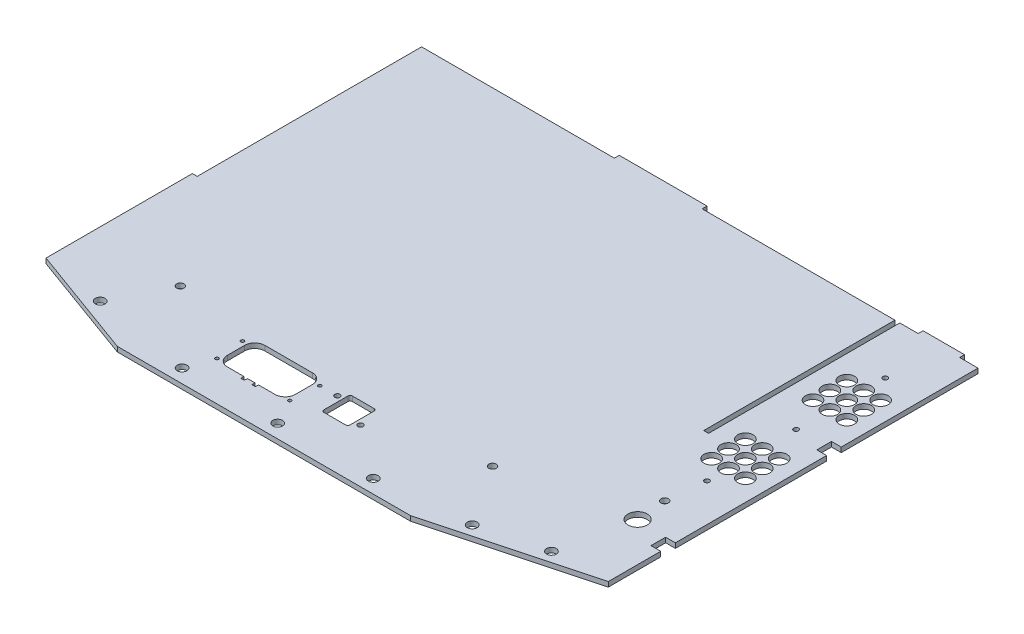
SolidWorks part; units mm, degrees
material "6061-T6 (SS)"
ref_plane "X-Y Datum" through (0, 0, 0) normal (0, 0, 1) x (1, 0, 0)
ref_plane "X-Z Datum" through (0, 0, 0) normal (0, 1, 0) x (1, 0, 0)
ref_plane "Y-Z Datum" through (0, 0, 0) normal (1, 0, 0) x (0, 0, -1)
sketch "Sketch1" plane through (0, 0, 0) normal (0, 0, 1) x (1, 0, 0)
  line L1 (-154.0408, -1.5875) -> (154.0408, -1.5875)
  line L2 (-154.0408, -1.5875) -> (-154.0408, 1.5875)
  line L3 (-154.0408, 1.5875) -> (154.0408, 1.5875)
  line L4 (154.0408, -1.5875) -> (154.0408, 1.5875)
  line L5 (-154.0408, -1.5875) -> (154.0408, 1.5875) construction
  line L6 (-154.0408, 1.5875) -> (154.0408, -1.5875) construction
  point P0 (0, 0)
  dimension "D1" = 3.175
  dimension "D2" = 308.0817
extrude "Boss-Extrude1" add sketch "Sketch1" along normal blind 267.83
sketch "Sketch3" plane through (154.0408, 0, 0) normal (1, 0, 0) x (0, 0, -1)
  line L9 (0, -1.5875) -> (0, 1.5875)
  line L10 (0, 1.5875) -> (-267.83, 1.5875)
  line L11 (-267.83, 1.5875) -> (-267.83, -1.5875)
  line L12 (-267.83, -1.5875) -> (0, -1.5875)
  line L13 (0, -1.5875) -> (0, 1.5875)
  line L14 (0, 1.5875) -> (-267.83, 1.5875)
  line L15 (-267.83, 1.5875) -> (-267.83, -1.5875)
  line L16 (-267.83, -1.5875) -> (0, -1.5875)
  dimension "D1" = 0
extrude "Boss-Extrude3" add sketch "Sketch3" along normal blind 3.175
sketch "Sketch4" plane through (0, 0, 267.83) normal (0, 0, 1) x (1, 0, 0)
  line L1 (157.2158, -1.5875) -> (208.1047, -1.5875)
  line L2 (157.2158, -1.5875) -> (157.2158, 1.5875)
  line L3 (157.2158, 1.5875) -> (208.1047, 1.5875)
  line L4 (208.1047, -1.5875) -> (208.1047, 1.5875)
  dimension "D1" = 3.175
  dimension "D2" = 50.8889
extrude "Boss-Extrude4" add sketch "Sketch4" against normal blind 267.83
sketch "Sketch6" plane through (0, 1.5875, 0) normal (0, 1, 0) x (1, 0, 0)
  line L0 (106.5047, -267.83) -> (106.5047, -228.46)
  line L1 (208.1047, -267.83) -> (-154.0408, -267.83) construction
  line L2 (208.1047, -228.46) -> (106.5047, -228.46)
  line L3 (208.1047, 0) -> (208.1047, -267.83) construction
  line L5 (106.5047, -267.83) -> (208.1047, -240.6064)
  line L7 (208.1047, -228.46) -> (208.1047, -240.6064)
  line L8 (208.1047, 0) -> (208.1047, -267.83) construction
  line L9 (208.1047, -267.83) -> (-154.0408, -267.83) construction
  line M9 (-154.0408, -267.83) -> (208.1047, -267.83)
  line M10 (208.1047, -267.83) -> (208.1047, 0)
  dimension "D1" = 39.37
  dimension "D2" = 101.6
  dimension "D3" = 15
extrude "Cut-Extrude1" cut sketch "Sketch6" against normal through all contours L5 M9 M10
sketch "Sketch19" plane through (0, 1.5875, 0) normal (0, 1, 0) x (1, 0, 0)
  line L0 (208.1047, 0) -> (208.1047, -240.6064) construction
  line L1 (208.1047, 0) -> (-154.0408, 0) construction
  line L3 (164.1047, -82.5) -> (204.1047, -82.5)
  line L4 (164.1047, -82.5) -> (164.1047, -42.5)
  line L5 (164.1047, -42.5) -> (204.1047, -42.5)
  line L6 (204.1047, -82.5) -> (204.1047, -42.5)
  line L7 (164.1047, -82.5) -> (204.1047, -42.5) construction
  line L8 (164.1047, -42.5) -> (204.1047, -82.5) construction
  circle A0 centre (172.4867, -49.7748) radius 5
  dimension "D5" = 10
  dimension "D6" = 7.2748
  dimension "D1" = 40
  dimension "D2" = 40
  dimension "D3" = 42.5
  dimension "D4" = 8.382
  dimension "D7" = 4
extrude "Cut-Extrude5" cut sketch "Sketch19" against normal through all contours A0
pattern_linear "LPattern1" count 3 spacing 11 along (1, 0, 0) of "Cut-Extrude5"
pattern_linear "LPattern2" count 3 spacing 11 along (0, 0, 1) of "LPattern1", "Cut-Extrude5"
pattern_linear "LPattern3" count 2 spacing 66 along (0, 0, 1) of "LPattern2", "Cut-Extrude5", "LPattern1"
sketch "Sketch21" plane through (-154.0408, 0, 0) normal (-1, 0, 0) x (0, 0, 1)
  line L14 (0, -1.5875) -> (267.83, -1.5875)
  line L15 (267.83, -1.5875) -> (267.83, 1.5875)
  line L16 (267.83, 1.5875) -> (0, 1.5875)
  line L17 (0, 1.5875) -> (0, -1.5875)
  line L18 (0, -1.5875) -> (267.83, -1.5875)
  line L20 (267.83, 1.5875) -> (0, 1.5875)
  line L21 (0, 1.5875) -> (0, -1.5875)
  line L22 (267.83, -1.5875) -> (267.83, 1.5875)
  dimension "D1" = 0
extrude "Boss-Extrude5" add sketch "Sketch21" along normal blind 3.175
sketch "Sketch11" plane through (0, -1.5875, 0) normal (0, -1, 0) x (1, 0, 0)
  line L0 (-84.2547, 267.83) -> (-84.2547, 241.2743)
  line L3 (-157.2158, 267.83) -> (106.5047, 267.83) construction
  line L4 (-157.2158, 241.2743) -> (-84.2547, 267.83)
  line L5 (-157.2158, 241.2743) -> (-84.2547, 241.2743)
  line L7 (-157.2158, 0) -> (-157.2158, 267.83) construction
  dimension "D1" = 26.5557
  dimension "D2" = 20
extrude "Cut-Extrude3" cut sketch "Sketch11" against normal through all
sketch "Sketch36" plane through (0, 1.5875, 0) normal (0, 1, 0) x (1, 0, 0)
  circle A1 centre (183.4867, -35.7748) radius 2.4 construction
  circle A2 centre (183.4867, -35.7748) radius 1.5875
  dimension "D1" = 3.175
extrude "Cut-Extrude12" cut sketch "Sketch36" against normal through all both and the other way through all
pattern_linear "LPattern4" count 3 spacing 58 along (0, 0, 1) of "Cut-Extrude12"
sketch "Sketch38" plane through (0, 1.5875, 0) normal (0, 1, 0) x (1, 0, 0)
  point P0 (180.965, -176.776)
  point P1 (105.4291, -213.285)
  point P2 (105.4291, -213.285)
  point P3 (-97.7709, -213.285)
hole_wizard "M4 Clearance Hole1" positions "Sketch38" profile "Sketch39" hole size "M4" standard "ANSI Metric" end condition through all
sketch "Sketch39" plane through (180.965, 1.5875, 176.776) normal (1, 0, 0) x (0, 0, 1)
  line L0 (0, 0) -> (0, 3.175)
  line L1 (0, 3.175) -> (2.4, 3.175)
  line L2 (2.4, 3.175) -> (2.4, 0)
  line L5 (2.4, 0) -> (0, 0)
  line L11 (0, -6.35) -> (0, 107.95) construction
  dimension "Thru Hole Dia." = 4.8
  dimension "Thru Hole Depth" = 3.175
sketch "Sketch40" plane through (0, 1.5875, 0) normal (0, 1, 0) x (1, 0, 0)
  circle A0 centre (172.5447, -242.093) radius 3.175
  circle A1 centre (131.9047, -252.9824) radius 3.175
  circle A2 centre (73.4847, -258.94) radius 3.175
  circle A3 centre (11.2547, -258.94) radius 3.175
  circle A4 centre (-50.9753, -258.94) radius 3.175
  circle A5 centre (-115.3222, -247.9214) radius 3.175
  point P0 (-115.3222, -247.9214)
  point P1 (-50.9753, -258.94)
  point P3 (11.2547, -258.94)
  point P5 (73.4847, -258.94)
  point P7 (131.9047, -252.9824)
  point P9 (172.5447, -242.093)
  dimension "D1" = 6.35
extrude "Cut-Extrude13" cut sketch "Sketch40" against normal through all
sketch "Sketch41" plane through (0, 1.5875, 0) normal (0, 1, 0) x (1, 0, 0)
  line L0 (-25.8051, -243.2308) -> (-25.6301, -245.2308) construction
  line L1 (-25.6301, -245.2308) -> (-24.1801, -245.2308) construction
  line L2 (-24.1801, -245.2308) -> (-24.0051, -243.2308) construction
  line L3 (-18.4301, -245.2308) -> (-16.9801, -245.2308) construction
  line L4 (-16.9801, -245.2308) -> (-16.8051, -243.2308) construction
  line L5 (-18.6051, -243.2308) -> (-18.4301, -245.2308) construction
  line L6 (-16.8051, -243.2308) -> (-5.8051, -243.2308) construction
  line L7 (0.3949, -237.0308) -> (0.3949, -225.8308) construction
  line L8 (-5.8051, -219.6308) -> (-36.8051, -219.6308) construction
  line L9 (-43.0051, -225.8308) -> (-43.0051, -237.0308) construction
  line L10 (-36.8051, -243.2308) -> (-25.8051, -243.2308) construction
  line L11 (-24.0051, -243.2308) -> (-18.6051, -243.2308) construction
  line L12 (-25.8051, -243.2308) -> (-25.6301, -245.2308) construction
  line L13 (-25.6301, -245.2308) -> (-24.1801, -245.2308) construction
  line L14 (-24.1801, -245.2308) -> (-24.0051, -243.2308) construction
  line L15 (-18.4301, -245.2308) -> (-16.9801, -245.2308) construction
  line L16 (-16.9801, -245.2308) -> (-16.8051, -243.2308) construction
  line L17 (-18.6051, -243.2308) -> (-18.4301, -245.2308) construction
  line L18 (-16.8051, -243.2308) -> (-5.8051, -243.2308) construction
  line L19 (0.3949, -237.0308) -> (0.3949, -225.8308) construction
  line L20 (-5.8051, -219.6308) -> (-36.8051, -219.6308) construction
  line L21 (-43.0051, -225.8308) -> (-43.0051, -237.0308) construction
  line L22 (-36.8051, -243.2308) -> (-25.8051, -243.2308) construction
  line L23 (-24.0051, -243.2308) -> (-18.6051, -243.2308) construction
  line L24 (20.242, -220.3508) -> (34.292, -220.3508) construction
  line L25 (34.292, -219.7008) -> (20.242, -219.7008) construction
  line L26 (19.142, -220.8008) -> (19.142, -236.3508) construction
  line L27 (19.792, -236.3508) -> (19.792, -220.8008) construction
  line L28 (20.242, -237.4508) -> (34.292, -237.4508) construction
  line L29 (34.292, -236.8008) -> (20.242, -236.8008) construction
  line L30 (34.742, -220.8008) -> (34.742, -236.3508) construction
  line L31 (35.392, -236.3508) -> (35.392, -220.8008) construction
  line L32 (20.242, -220.3508) -> (34.292, -220.3508) construction
  line L33 (34.292, -219.7008) -> (20.242, -219.7008) construction
  line L34 (19.142, -220.8008) -> (19.142, -236.3508) construction
  line L35 (19.792, -236.3508) -> (19.792, -220.8008) construction
  line L36 (20.242, -237.4508) -> (34.292, -237.4508) construction
  line L37 (34.292, -236.8008) -> (20.242, -236.8008) construction
  line L38 (34.742, -220.8008) -> (34.742, -236.3508) construction
  line L39 (35.392, -236.3508) -> (35.392, -220.8008) construction
  line L40 (15.267, -225.0758) -> (15.267, -223.0758) construction
  line L41 (39.267, -234.0758) -> (39.267, -232.0758) construction
  line L42 (-26.1542, -243.6118) -> (-25.9792, -245.6118)
  line L43 (-25.9792, -245.6118) -> (-23.8309, -245.6118)
  line L44 (-23.8309, -245.6118) -> (-23.656, -243.6118)
  line L45 (-23.656, -243.6118) -> (-18.9542, -243.6118)
  line L46 (-18.9542, -243.6118) -> (-18.7792, -245.6118)
  line L47 (-18.7792, -245.6118) -> (-16.6309, -245.6118)
  line L48 (-16.6309, -245.6118) -> (-16.456, -243.6118)
  line L49 (-16.456, -243.6118) -> (-5.8051, -243.6118)
  line L50 (0.7759, -237.0308) -> (0.7759, -225.8308)
  line L51 (-5.8051, -219.2498) -> (-36.8051, -219.2498)
  line L52 (-43.3861, -225.8308) -> (-43.3861, -237.0308)
  line L53 (-36.8051, -243.6118) -> (-26.1542, -243.6118)
  line L54 (18.761, -220.8008) -> (18.761, -236.3508)
  line L55 (20.242, -237.8318) -> (34.292, -237.8318)
  line L56 (35.773, -236.3508) -> (35.773, -220.8008)
  line L57 (34.292, -219.3198) -> (20.242, -219.3198)
  spline S0 degree 3 poles (-5.8051, -243.2308) (-2.1732, -243.2308) (0.3949, -240.6627) (0.3949, -237.0308) knots 0 0 0 0 1 1 1 1 weights 1 0.804738 0.804738 1 construction
  spline S1 degree 3 poles (0.3949, -225.8308) (0.3949, -222.1989) (-2.1732, -219.6308) (-5.8051, -219.6308) knots 0 0 0 0 1 1 1 1 weights 1 0.804738 0.804738 1 construction
  spline S2 degree 3 poles (-36.8051, -219.6308) (-40.4369, -219.6308) (-43.0051, -222.1989) (-43.0051, -225.8308) knots 0 0 0 0 1 1 1 1 weights 1 0.804738 0.804738 1 construction
  spline S3 degree 3 poles (-43.0051, -237.0308) (-43.0051, -240.6627) (-40.4369, -243.2308) (-36.8051, -243.2308) knots 0 0 0 0 1 1 1 1 weights 1 0.804738 0.804738 1 construction
  spline S4 degree 3 poles (-5.8051, -243.2308) (-2.1732, -243.2308) (0.3949, -240.6627) (0.3949, -237.0308) knots 0 0 0 0 1 1 1 1 weights 1 0.804738 0.804738 1 construction
  spline S5 degree 3 poles (0.3949, -225.8308) (0.3949, -222.1989) (-2.1732, -219.6308) (-5.8051, -219.6308) knots 0 0 0 0 1 1 1 1 weights 1 0.804738 0.804738 1 construction
  spline S6 degree 3 poles (-36.8051, -219.6308) (-40.4369, -219.6308) (-43.0051, -222.1989) (-43.0051, -225.8308) knots 0 0 0 0 1 1 1 1 weights 1 0.804738 0.804738 1 construction
  spline S7 degree 3 poles (-43.0051, -237.0308) (-43.0051, -240.6627) (-40.4369, -243.2308) (-36.8051, -243.2308) knots 0 0 0 0 1 1 1 1 weights 1 0.804738 0.804738 1 construction
  spline S8 degree 3 poles (34.292, -220.3508) (34.5556, -220.3508) (34.742, -220.5372) (34.742, -220.8008) knots 0 0 0 0 1 1 1 1 weights 1 0.804738 0.804738 1 construction
  spline S9 degree 3 poles (35.392, -220.8008) (35.392, -220.1564) (34.9364, -219.7008) (34.292, -219.7008) knots 0 0 0 0 1 1 1 1 weights 1 0.804738 0.804738 1 construction
  spline S10 degree 3 poles (20.242, -219.7008) (19.5976, -219.7008) (19.142, -220.1564) (19.142, -220.8008) knots 0 0 0 0 1 1 1 1 weights 1 0.804738 0.804738 1 construction
  spline S11 degree 3 poles (19.792, -220.8008) (19.792, -220.5372) (19.9784, -220.3508) (20.242, -220.3508) knots 0 0 0 0 1 1 1 1 weights 1 0.804738 0.804738 1 construction
  spline S12 degree 3 poles (19.142, -236.3508) (19.142, -236.9952) (19.5976, -237.4508) (20.242, -237.4508) knots 0 0 0 0 1 1 1 1 weights 1 0.804738 0.804738 1 construction
  spline S13 degree 3 poles (20.242, -236.8008) (19.9784, -236.8008) (19.792, -236.6144) (19.792, -236.3508) knots 0 0 0 0 1 1 1 1 weights 1 0.804738 0.804738 1 construction
  spline S14 degree 3 poles (34.292, -237.4508) (34.9364, -237.4508) (35.392, -236.9952) (35.392, -236.3508) knots 0 0 0 0 1 1 1 1 weights 1 0.804738 0.804738 1 construction
  spline S15 degree 3 poles (34.742, -236.3508) (34.742, -236.6144) (34.5556, -236.8008) (34.292, -236.8008) knots 0 0 0 0 1 1 1 1 weights 1 0.804738 0.804738 1 construction
  spline S16 degree 3 poles (34.292, -220.3508) (34.5556, -220.3508) (34.742, -220.5372) (34.742, -220.8008) knots 0 0 0 0 1 1 1 1 weights 1 0.804738 0.804738 1 construction
  spline S17 degree 3 poles (35.392, -220.8008) (35.392, -220.1564) (34.9364, -219.7008) (34.292, -219.7008) knots 0 0 0 0 1 1 1 1 weights 1 0.804738 0.804738 1 construction
  spline S18 degree 3 poles (20.242, -219.7008) (19.5976, -219.7008) (19.142, -220.1564) (19.142, -220.8008) knots 0 0 0 0 1 1 1 1 weights 1 0.804738 0.804738 1 construction
  spline S19 degree 3 poles (19.792, -220.8008) (19.792, -220.5372) (19.9784, -220.3508) (20.242, -220.3508) knots 0 0 0 0 1 1 1 1 weights 1 0.804738 0.804738 1 construction
  spline S20 degree 3 poles (19.142, -236.3508) (19.142, -236.9952) (19.5976, -237.4508) (20.242, -237.4508) knots 0 0 0 0 1 1 1 1 weights 1 0.804738 0.804738 1 construction
  spline S21 degree 3 poles (20.242, -236.8008) (19.9784, -236.8008) (19.792, -236.6144) (19.792, -236.3508) knots 0 0 0 0 1 1 1 1 weights 1 0.804738 0.804738 1 construction
  spline S22 degree 3 poles (34.292, -237.4508) (34.9364, -237.4508) (35.392, -236.9952) (35.392, -236.3508) knots 0 0 0 0 1 1 1 1 weights 1 0.804738 0.804738 1 construction
  spline S23 degree 3 poles (34.742, -236.3508) (34.742, -236.6144) (34.5556, -236.8008) (34.292, -236.8008) knots 0 0 0 0 1 1 1 1 weights 1 0.804738 0.804738 1 construction
  spline S24 degree 3 poles (-47.5901, -224.1308) (-47.5901, -221.9608) (-45.4201, -221.9608) (-45.4201, -224.1308) knots 0 0 0 0 1 1 1 1 weights 1 0.333333 0.333333 1 construction
  spline S25 degree 3 poles (-45.4201, -224.1308) (-45.4201, -226.3008) (-47.5901, -226.3008) (-47.5901, -224.1308) knots 0 0 0 0 1 1 1 1 weights 1 0.333333 0.333333 1 construction
  spline S26 degree 3 poles (-43.9201, -242.2308) (-43.9201, -244.4008) (-46.0901, -244.4008) (-46.0901, -242.2308) knots 0 0 0 0 1 1 1 1 weights 1 0.333333 0.333333 1 construction
  spline S27 degree 3 poles (-46.0901, -242.2308) (-46.0901, -240.0608) (-43.9201, -240.0608) (-43.9201, -242.2308) knots 0 0 0 0 1 1 1 1 weights 1 0.333333 0.333333 1 construction
  spline S28 degree 3 poles (3.4799, -242.2308) (3.4799, -244.4008) (1.3099, -244.4008) (1.3099, -242.2308) knots 0 0 0 0 1 1 1 1 weights 1 0.333333 0.333333 1 construction
  spline S29 degree 3 poles (1.3099, -242.2308) (1.3099, -240.0608) (3.4799, -240.0608) (3.4799, -242.2308) knots 0 0 0 0 1 1 1 1 weights 1 0.333333 0.333333 1 construction
  spline S30 degree 3 poles (4.9799, -224.1308) (4.9799, -226.3008) (2.8099, -226.3008) (2.8099, -224.1308) knots 0 0 0 0 1 1 1 1 weights 1 0.333333 0.333333 1 construction
  spline S31 degree 3 poles (2.8099, -224.1308) (2.8099, -221.9608) (4.9799, -221.9608) (4.9799, -224.1308) knots 0 0 0 0 1 1 1 1 weights 1 0.333333 0.333333 1 construction
  spline S32 degree 3 poles (-47.5901, -224.1308) (-47.5901, -221.9608) (-45.4201, -221.9608) (-45.4201, -224.1308) knots 0 0 0 0 1 1 1 1 weights 1 0.333333 0.333333 1
  spline S33 degree 3 poles (-45.4201, -224.1308) (-45.4201, -226.3008) (-47.5901, -226.3008) (-47.5901, -224.1308) knots 0 0 0 0 1 1 1 1 weights 1 0.333333 0.333333 1
  spline S34 degree 3 poles (-43.9201, -242.2308) (-43.9201, -244.4008) (-46.0901, -244.4008) (-46.0901, -242.2308) knots 0 0 0 0 1 1 1 1 weights 1 0.333333 0.333333 1
  spline S35 degree 3 poles (-46.0901, -242.2308) (-46.0901, -240.0608) (-43.9201, -240.0608) (-43.9201, -242.2308) knots 0 0 0 0 1 1 1 1 weights 1 0.333333 0.333333 1
  spline S36 degree 3 poles (3.4799, -242.2308) (3.4799, -244.4008) (1.3099, -244.4008) (1.3099, -242.2308) knots 0 0 0 0 1 1 1 1 weights 1 0.333333 0.333333 1
  spline S37 degree 3 poles (1.3099, -242.2308) (1.3099, -240.0608) (3.4799, -240.0608) (3.4799, -242.2308) knots 0 0 0 0 1 1 1 1 weights 1 0.333333 0.333333 1
  spline S38 degree 3 poles (4.9799, -224.1308) (4.9799, -226.3008) (2.8099, -226.3008) (2.8099, -224.1308) knots 0 0 0 0 1 1 1 1 weights 1 0.333333 0.333333 1
  spline S39 degree 3 poles (2.8099, -224.1308) (2.8099, -221.9608) (4.9799, -221.9608) (4.9799, -224.1308) knots 0 0 0 0 1 1 1 1 weights 1 0.333333 0.333333 1
  spline S40 degree 3 poles (15.267, -225.0758) (17.267, -225.0758) (17.267, -223.0758) (15.267, -223.0758) knots 0 0 0 0 1 1 1 1 weights 1 0.333333 0.333333 1 construction
  spline S41 degree 3 poles (15.267, -223.0758) (13.267, -223.0758) (13.267, -225.0758) (15.267, -225.0758) knots 0 0 0 0 1 1 1 1 weights 1 0.333333 0.333333 1 construction
  spline S42 degree 3 poles (15.267, -225.0758) (17.267, -225.0758) (17.267, -223.0758) (15.267, -223.0758) knots 0 0 0 0 1 1 1 1 weights 1 0.333333 0.333333 1 construction
  spline S43 degree 3 poles (15.267, -223.0758) (13.267, -223.0758) (13.267, -225.0758) (15.267, -225.0758) knots 0 0 0 0 1 1 1 1 weights 1 0.333333 0.333333 1 construction
  spline S44 degree 3 poles (39.267, -234.0758) (41.267, -234.0758) (41.267, -232.0758) (39.267, -232.0758) knots 0 0 0 0 1 1 1 1 weights 1 0.333333 0.333333 1 construction
  spline S45 degree 3 poles (39.267, -232.0758) (37.267, -232.0758) (37.267, -234.0758) (39.267, -234.0758) knots 0 0 0 0 1 1 1 1 weights 1 0.333333 0.333333 1 construction
  spline S46 degree 3 poles (39.267, -234.0758) (41.267, -234.0758) (41.267, -232.0758) (39.267, -232.0758) knots 0 0 0 0 1 1 1 1 weights 1 0.333333 0.333333 1 construction
  spline S47 degree 3 poles (39.267, -232.0758) (37.267, -232.0758) (37.267, -234.0758) (39.267, -234.0758) knots 0 0 0 0 1 1 1 1 weights 1 0.333333 0.333333 1 construction
  spline S48 degree 1 poles (-5.8051, -243.6118) (0.7759, -237.0308) knots 0 0 1 1 construction
  spline S49 degree 1 poles (0.7759, -225.8308) (-5.8051, -219.2498) knots 0 0 1 1 construction
  spline S50 degree 1 poles (-36.8051, -219.2498) (-43.3861, -225.8308) knots 0 0 1 1 construction
  spline S51 degree 1 poles (-43.3861, -237.0308) (-36.8051, -243.6118) knots 0 0 1 1 construction
  spline S52 degree 3 poles (-5.8051, -243.6118) (-5.4042, -243.6118) (-4.6186, -243.5426) (-2.9592, -243.079) (-1.014, -241.8219) (0.2432, -239.8767) (0.7067, -238.2173) (0.7759, -237.4316) (0.7759, -237.0308) knots 0 0 0 0 0.125 0.25 0.5 0.75 0.875 1 1 1 1
  spline S53 degree 3 poles (0.7759, -225.8308) (0.7759, -225.43) (0.7067, -224.6443) (0.2432, -222.9849) (-1.014, -221.0397) (-2.9592, -219.7826) (-4.6186, -219.319) (-5.4042, -219.2498) (-5.8051, -219.2498) knots 0 0 0 0 0.125 0.25 0.5 0.75 0.875 1 1 1 1
  spline S54 degree 3 poles (-36.8051, -219.2498) (-37.2059, -219.2498) (-37.9916, -219.319) (-39.651, -219.7826) (-41.5961, -221.0397) (-42.8533, -222.9849) (-43.3168, -224.6443) (-43.3861, -225.43) (-43.3861, -225.8308) knots 0 0 0 0 0.125 0.25 0.5 0.75 0.875 1 1 1 1
  spline S55 degree 3 poles (-43.3861, -237.0308) (-43.3861, -237.4316) (-43.3168, -238.2173) (-42.8533, -239.8767) (-41.5961, -241.8219) (-39.651, -243.079) (-37.9916, -243.5426) (-37.2059, -243.6118) (-36.8051, -243.6118) knots 0 0 0 0 0.125 0.25 0.5 0.75 0.875 1 1 1 1
  spline S56 degree 1 poles (18.761, -236.3508) (20.242, -237.8318) knots 0 0 1 1 construction
  spline S57 degree 1 poles (34.292, -237.8318) (35.773, -236.3508) knots 0 0 1 1 construction
  spline S58 degree 3 poles (18.761, -236.3508) (18.761, -236.5358) (18.8246, -236.8976) (19.1622, -237.4306) (19.6953, -237.7682) (20.057, -237.8318) (20.242, -237.8318) knots 0 0 0 0 0.25 0.5 0.75 1 1 1 1
  spline S59 degree 3 poles (34.292, -237.8318) (34.477, -237.8318) (34.8387, -237.7682) (35.3718, -237.4306) (35.7094, -236.8976) (35.773, -236.5358) (35.773, -236.3508) knots 0 0 0 0 0.25 0.5 0.75 1 1 1 1
  spline S60 degree 1 poles (35.773, -220.8008) (34.292, -219.3198) knots 0 0 1 1 construction
  spline S61 degree 1 poles (20.242, -219.3198) (18.761, -220.8008) knots 0 0 1 1 construction
  spline S62 degree 3 poles (35.773, -220.8008) (35.773, -220.6158) (35.7094, -220.2541) (35.3718, -219.721) (34.8387, -219.3834) (34.477, -219.3198) (34.292, -219.3198) knots 0 0 0 0 0.25 0.5 0.75 1 1 1 1
  spline S63 degree 3 poles (20.242, -219.3198) (20.057, -219.3198) (19.6953, -219.3834) (19.1622, -219.721) (18.8246, -220.2541) (18.761, -220.6158) (18.761, -220.8008) knots 0 0 0 0 0.25 0.5 0.75 1 1 1 1
  point P40 (39.267, -233.0758)
  point P44 (15.267, -224.0758)
  dimension "D1" = 0.381
  dimension "D2" = 0.381
  dimension "D3" = 0.381
extrude "Cut-Extrude15" cut sketch "Sketch41" against normal through all contours L57 S63 L54 S58 L55 S59 L56 S62 | L52 S55 L53 L42 L43 L44 L45 L46 L47 L48 L49 S52 L50 S53 L51 S54 | S37 S36 | S39 S38 | S35 S34 | S33 S32
hole_wizard "M3 Clearance Hole1" positions "Sketch44" profile "Sketch43" hole size "M3" standard "ANSI Metric" end condition through all
sketch "Sketch44" plane through (0, 1.5875, 0) normal (0, 1, 0) x (1, 0, 0)
  point P0 (39.267, -233.0758)
  point P3 (15.267, -224.0758)
sketch "Sketch43" plane through (39.267, 1.5875, 233.0758) normal (1, 0, 0) x (0, 0, 1)
  line L0 (0, 0) -> (0, 3.175)
  line L1 (0, 3.175) -> (1.7, 3.175)
  line L2 (1.7, 3.175) -> (1.7, 0)
  line L5 (1.7, 0) -> (0, 0)
  line L11 (0, -6.35) -> (0, 107.95) construction
  dimension "Thru Hole Dia." = 3.4
  dimension "Thru Hole Depth" = 3.175
sketch "Sketch45" plane through (0, 0, 0) normal (0, 0, -1) x (-1, 0, 0)
  line L0 (28.6512, -1.6727) -> (-28.6512, -1.6727) construction
  line L1 (0, -1.5875) -> (0, 1.5875) construction
  line L2 (157.2158, -1.5875) -> (-208.1047, -1.5875) construction
  line L3 (-208.1047, 1.5875) -> (157.2158, 1.5875) construction
  line L4 (-169.0911, -1.6637) -> (-196.231, -1.6637) construction
  line L5 (-28.575, 1.5875) -> (28.575, 1.5875)
  line L6 (-28.575, 1.5875) -> (-28.575, -1.5875)
  line L7 (-28.575, -1.5875) -> (28.575, -1.5875)
  line L8 (28.575, 1.5875) -> (28.575, -1.5875)
  line L9 (-28.575, 1.5875) -> (28.575, -1.5875) construction
  line L10 (-28.575, -1.5875) -> (28.575, 1.5875) construction
  line L11 (-182.661, -1.5875) -> (-182.661, 1.5875) construction
  line L12 (-157.216, -1.5875) -> (-195.316, -1.5875) construction
  line L13 (-170.9867, 1.5875) -> (-195.9867, 1.5875) construction
  line L15 (-196.1548, 1.5875) -> (-169.1673, 1.5875)
  line L16 (-196.1548, 1.5875) -> (-196.1548, -1.5875)
  line L17 (-196.1548, -1.5875) -> (-169.1673, -1.5875)
  line L18 (-169.1673, 1.5875) -> (-169.1673, -1.5875)
  line L19 (-196.1548, 1.5875) -> (-169.1673, -1.5875) construction
  line L20 (-196.1548, -1.5875) -> (-169.1673, 1.5875) construction
  point P0 (0, -1.6727)
  point P10 (0, 0)
  point P15 (-182.661, -1.6637)
  point P24 (-182.661, 0)
  dimension "D1" = 57.15
  dimension "D2" = 26.9875
extrude "Boss-Extrude6" add sketch "Sketch45" along normal blind 3.175
sketch "Sketch46" plane through (0, 1.5875, 0) normal (0, 1, 0) x (1, 0, 0)
  line L0 (154.041, -124.442) -> (157.216, -124.442) construction
  line L1 (154.041, -124.442) -> (154.041, -50.8) construction
  line L2 (157.216, -124.442) -> (157.216, -50.8) construction
  line L3 (154.041, -124.442) -> (157.216, -124.442)
  line L4 (154.041, -124.442) -> (154.041, 0)
  line L5 (157.216, -124.442) -> (157.216, 0)
  line L6 (169.1673, 0) -> (28.575, 0) construction
  line L7 (154.041, 0) -> (157.216, 0)
  line L8 (153.9648, -124.5182) -> (153.9648, 0.0762)
  line L9 (153.9648, 0.0762) -> (157.2922, 0.0762)
  line L10 (157.2922, -124.5182) -> (157.2922, 0.0762)
  line L11 (153.9648, -124.5182) -> (157.2922, -124.5182)
  dimension "D1" = 0.0762
extrude "Cut-Extrude16" cut sketch "Sketch46" against normal through all contours L7 L4 L3 L5
sketch "Sketch47" plane through (0, 1.5875, 0) normal (0, 1, 0) x (1, 0, 0)
  line L0 (-157.292, -146.1005) -> (-153.9646, -146.1005)
  line L1 (-157.2158, 0) -> (-154.0408, 0)
  line L2 (-157.2158, 0) -> (-157.2158, -146.0243)
  line L3 (-157.2158, -146.0243) -> (-154.0408, -146.0243)
  line L4 (-154.0408, 0) -> (-154.0408, -146.0243)
  line L5 (-153.9646, 0.0762) -> (-153.9646, -146.1005)
  line L6 (-157.292, 0.0762) -> (-153.9646, 0.0762)
  line L7 (-157.292, 0.0762) -> (-157.292, -146.1005)
  dimension "D1" = 3.175
  dimension "D2" = 95.25
  dimension "D3" = 0.0762
extrude "Cut-Extrude17" cut sketch "Sketch47" against normal through all contours L4 L1 L2 L3
sketch "Sketch48" plane through (0, 1.5875, 0) normal (0, 1, 0) x (1, 0, 0)
  line L0 (208.1809, -196.8861) -> (201.6785, -196.8861)
  line L1 (201.6785, -196.8861) -> (201.6785, -206.5635)
  line L2 (201.6785, -206.5635) -> (208.1809, -206.5635)
  line L3 (208.1809, -206.5635) -> (208.1809, -196.8861)
  line L4 (201.7547, -196.9623) -> (201.7547, -206.4873)
  line L5 (201.7547, -206.4873) -> (208.1047, -206.4873)
  line L6 (208.1047, -206.4873) -> (208.1047, -196.9623)
  line L7 (208.1047, -196.9623) -> (201.7547, -196.9623)
  line L8 (201.7547, -196.9623) -> (201.7547, -206.4873)
  line L9 (201.7547, -206.4873) -> (208.1047, -206.4873)
  line L10 (208.1047, -206.4873) -> (208.1047, -196.9623)
  line L11 (208.1047, -196.9623) -> (201.7547, -196.9623)
  line L12 (201.7547, -89.0123) -> (201.7547, -98.5373)
  line L13 (201.7547, -98.5373) -> (208.1047, -98.5373)
  line L14 (208.1047, -98.5373) -> (208.1047, -89.0123)
  line L15 (208.1047, -89.0123) -> (201.7547, -89.0123)
  line L16 (201.7547, -89.0123) -> (201.7547, -98.5373)
  line L17 (201.7547, -98.5373) -> (208.1047, -98.5373)
  line L18 (208.1047, -98.5373) -> (208.1047, -89.0123)
  line L19 (208.1047, -89.0123) -> (201.7547, -89.0123)
  line L20 (201.6785, -98.6135) -> (208.1809, -98.6135)
  line L21 (208.1809, -98.6135) -> (208.1809, -88.9361)
  line L22 (208.1809, -88.9361) -> (201.6785, -88.9361)
  line L23 (201.6785, -88.9361) -> (201.6785, -98.6135)
  dimension "D1" = 0
  dimension "D2" = 0
  dimension "D3" = 0.0762
extrude "Cut-Extrude18" cut sketch "Sketch48" against normal through all contours L16 L17 L18 L19 | L8 L9 L10 L11
sketch "Sketch49" plane through (0, 1.5875, 0) normal (0, 1, 0) x (1, 0, 0)
  circle A0 centre (182.661, -196.101) radius 6.25
  point P0 (182.661, -196.101)
  dimension "D1" = 12.5
extrude "Cut-Extrude19" cut sketch "Sketch49" against normal through all
